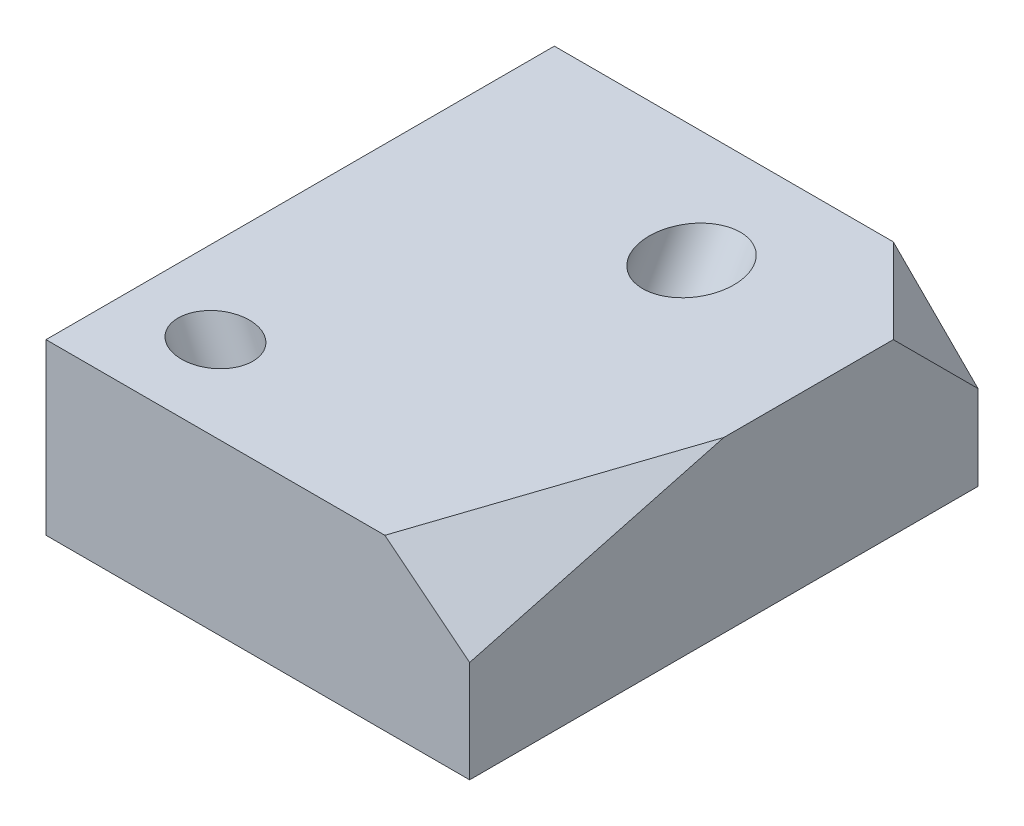
SolidWorks part; units mm, degrees
material "Cast Alloy Steel"
ref_plane "Front Plane" through (0, 0, 0) normal (0, 0, 1) x (1, 0, 0)
ref_plane "Top Plane" through (0, 0, 0) normal (0, 1, 0) x (1, 0, 0)
ref_plane "Right Plane" through (0, 0, 0) normal (1, 0, 0) x (0, 0, -1)
sketch "Sketch1" plane through (0, 0, 0) normal (0, 1, 0) x (1, 0, 0)
  line L1 (-63.5, -76.2) -> (63.5, -76.2)
  line L2 (-63.5, -76.2) -> (-63.5, 76.2)
  line L3 (-63.5, 76.2) -> (63.5, 76.2)
  line L4 (63.5, -76.2) -> (63.5, 76.2)
  line L5 (-63.5, -76.2) -> (63.5, 76.2) construction
  line L6 (-63.5, 76.2) -> (63.5, -76.2) construction
  point P0 (0, 0)
  dimension "D1" = 127
  dimension "D2" = 152.4
extrude "Boss-Extrude1" add sketch "Sketch1" along normal blind 50.8
sketch "Sketch2" plane through (63.5, 0, 0) normal (1, 0, 0) x (0, 0, -1)
  line L0 (-76.2, 30.48) -> (0, 50.8) construction
  line L1 (-76.2, 50.8) -> (-76.2, 0) construction
  line L2 (-76.2, 50.8) -> (76.2, 50.8) construction
  dimension "D1" = 20.32
  dimension "D2" = 76.2
ref_point "Point1" parameters "D1"=101.6
ref_plane "Plane1" through (47.5013, 59.3766, 15.8338) normal (0.6116, 0.7645, 0.2039) x (0.7912, -0.5909, -0.1576)
sketch "Sketch3" plane through (47.5013, 59.3766, 15.8338) normal (0.6116, 0.7645, 0.2039) x (0.7912, -0.5909, -0.1576)
  line L0 (-11.8826, -60.5378) -> (20.2212, 13.0893)
  line L1 (20.2212, 13.0893) -> (20.2212, -65.7735)
  line L2 (20.2212, -65.7735) -> (-11.8826, -60.5378)
extrude "Cut-Extrude1" cut sketch "Sketch3" along normal through all
ref_point "Point2" parameters "D1"=25.4
ref_point "Point3" parameters "D1"=25.4
ref_point "Point4" parameters "D1"=25.4
ref_plane "Plane2" through (55.0333, 55.0333, -55.0333) normal (0.5774, 0.5774, -0.5774) x (0.8165, -0.4082, 0.4082)
sketch "Sketch4" plane through (55.0333, 55.0333, -55.0333) normal (0.5774, 0.5774, -0.5774) x (0.8165, -0.4082, 0.4082)
  line L0 (-20.739, 17.9605) -> (10.3695, 35.921)
  line L1 (10.3695, 35.921) -> (10.3695, 0)
  line L2 (10.3695, 0) -> (-20.739, 17.9605)
extrude "Cut-Extrude2" cut sketch "Sketch4" along normal through all
sketch "Sketch5" plane through (0, 50.8, 0) normal (0, 1, 0) x (1, 0, 0)
  line L0 (-63.5, 76.2) -> (-63.5, -76.2) construction
  line L1 (-63.5, -76.2) -> (38.1, -76.2) construction
  point P0 (-38.1, -50.8)
  dimension "D1" = 25.4
  dimension "D2" = 25.4
ref_plane "Plane3" through (-30.799, 66.0487, 0) normal (-0.4226, 0.9063, 0) x (0, 0, 1)
sketch "Sketch6" plane through (-30.799, 66.0487, 0) normal (-0.4226, 0.9063, 0) x (0, 0, 1)
  circle A0 centre (50.8, -13.0613) radius 10.16
  dimension "D1" = 20.32
extrude "Cut-Extrude3" cut sketch "Sketch6" against normal through all contours A0
ref_plane "Plane4" through (0, 71.0956, -41.047) normal (0, 0.866, -0.5) x (-1, 0, 0)
sketch "Sketch7" plane through (0, 71.0956, -41.047) normal (0, 0.866, -0.5) x (-1, 0, 0)
  line L0 (63.5, -40.5911) -> (63.5, 91.3911) construction
  line L1 (63.5, 91.3911) -> (-38.1, 91.3911) construction
  circle A0 centre (-12.7, -10.2089) radius 12.7
  point P0 (-12.7, -10.2089)
  dimension "D3" = 25.4
  dimension "D1" = 76.2
  dimension "D2" = 101.6
extrude "Cut-Extrude4" cut sketch "Sketch7" against normal through all
